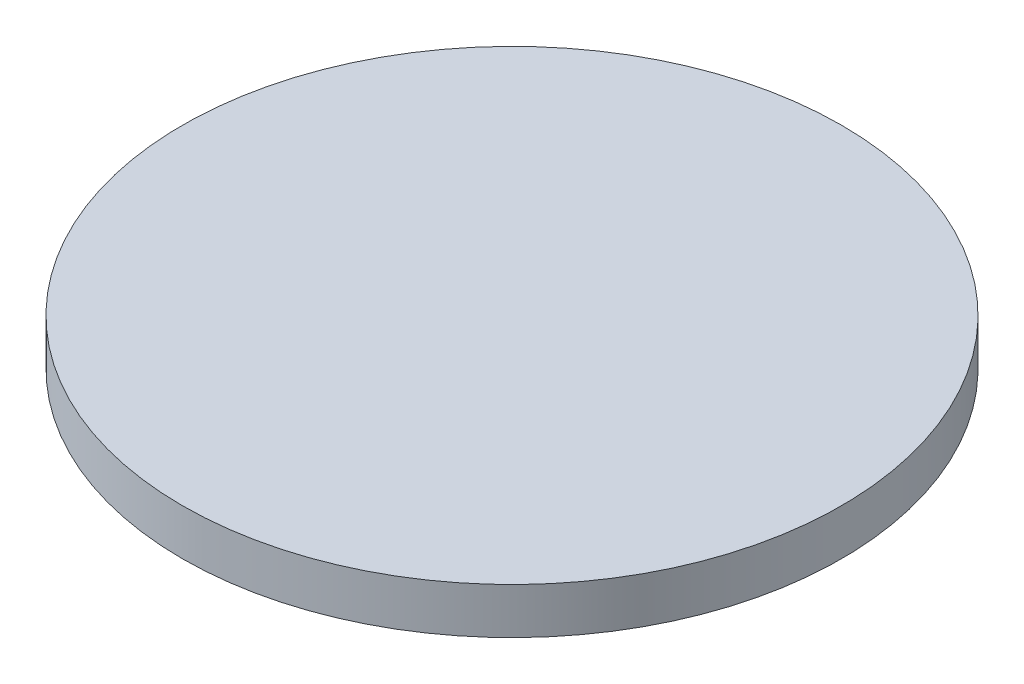
SolidWorks part; units mm, degrees
ref_plane "Front Plane" through (0, 0, 0) normal (0, 0, 1) x (1, 0, 0)
ref_plane "Top Plane" through (0, 0, 0) normal (0, 1, 0) x (1, 0, 0)
ref_plane "Right Plane" through (0, 0, 0) normal (1, 0, 0) x (0, 0, -1)
sketch "Sketch1" plane through (0, 0, 0) normal (0, 1, 0) x (1, 0, 0)
  circle A0 centre (0, 0) radius 21.5
  dimension "D1" = 43
extrude "Boss-Extrude1" add sketch "Sketch1" along normal blind 3
